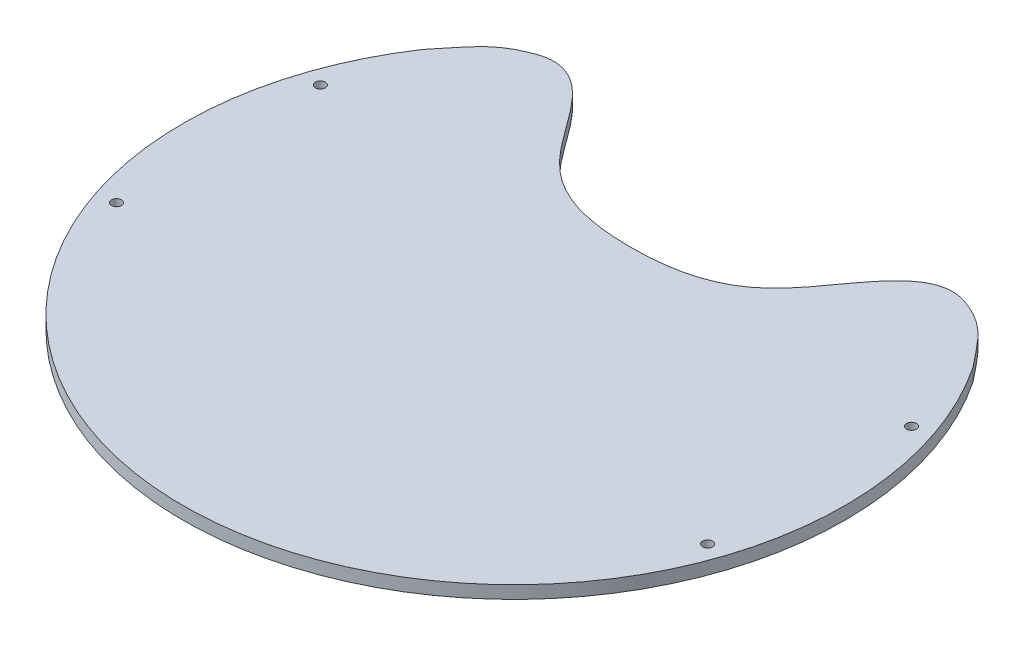
SolidWorks part; units mm, degrees
material "ABS"
ref_plane "Front Plane" through (0, 0, 0) normal (0, 0, 1) x (1, 0, 0)
ref_plane "Top Plane" through (0, 0, 0) normal (0, 1, 0) x (1, 0, 0)
ref_plane "Right Plane" through (0, 0, 0) normal (1, 0, 0) x (0, 0, -1)
sketch "Sketch1" plane through (0, 0, 0) normal (0, 1, 0) x (1, 0, 0)
  circle A0 centre (0, 0) radius 164.975
  dimension "D1" = 329.95
extrude "Boss-Extrude1" add sketch "Sketch1" along normal blind 6.35
ref_point "Point1"
sketch "Sketch2" plane through (0, 0, 0) normal (0, -1, 0) x (1, 0, 0)
  line L0 (0, -1000) -> (0, 49000) construction
  line L1 (-1000, 0) -> (49000, 0) construction
  circle A0 centre (147.32, -50.8) radius 4.7625 construction
  circle A1 centre (147.32, 50.8) radius 4.7625 construction
  circle A2 centre (-147.32, -50.8) radius 4.7625 construction
  circle A3 centre (-147.32, 50.8) radius 4.7625 construction
  point P0 (147.32, -50.8)
  dimension "D1" = 147.32
  dimension "D2" = 50.8
hole_wizard "#10 Clearance Hole1" positions "Sketch4" profile "Sketch3" hole size "#10" standard "Ansi Inch" end condition through all
sketch "Sketch4" plane through (0, 6.35, 0) normal (0, 1, 0) x (-1, 0, 0)
  point P1 (147.32, 50.8)
  point P4 (147.32, -50.8)
  point P7 (-147.32, -50.8)
  point P10 (-147.32, 50.8)
sketch "Sketch3" plane through (-147.32, 6.35, 50.8) normal (1, 0, 0) x (0, 0, 1)
  line L0 (0, 0) -> (0, 6.35)
  line L1 (0, 6.35) -> (2.4892, 6.35)
  line L2 (2.4892, 6.35) -> (2.4892, 0)
  line L5 (2.4892, 0) -> (0, 0)
  line L11 (0, -6.35) -> (0, 107.95) construction
  dimension "Thru Hole Dia." = 4.9784
  dimension "Thru Hole Depth" = 6.35
sketch "Sketch5" plane through (0, 6.35, 0) normal (0, 1, 0) x (1, 0, 0)
  line L0 (0, 201000) -> (0, -249000) construction
  line L1 (-50.8, -55.3589) -> (50.8, -55.3589) construction
  line L2 (-50.8, -55.3589) -> (-50.8, -156.9589) construction
  line L3 (-50.8, -156.9589) -> (50.8, -156.9589) construction
  line L4 (50.8, -55.3589) -> (50.8, -156.9589) construction
  line L5 (-50.8, -55.3589) -> (50.8, -156.9589) construction
  line L6 (-50.8, -156.9589) -> (50.8, -55.3589) construction
  line L7 (0, -106.1589) -> (0, 58.1068) construction
  circle A0 centre (0, 0) radius 164.975 construction
  circle A2 centre (147.32, 50.8) radius 2.4892 construction
  spline S0 degree 3 poles (-137.1735, 91.6525) (-125.7052, 105.9966) (-120.8705, 112.2721) (-90.3531, 124.7653) (-63.3632, 88.0034) (-42.1548, 58.1068) (0, 58.1068) knots 0 0 0 0 0.216331 0.275014 0.586828 1 1 1 1
  spline S1 degree 3 poles (137.1735, 91.6525) (125.7052, 105.9966) (120.8705, 112.2721) (90.3531, 124.7653) (63.3632, 88.0034) (42.1548, 58.1068) (0, 58.1068) knots 0 0 0 0 0.216331 0.275014 0.586828 1 1 1 1
  point P0 (0, -106.1589)
  dimension "D1" = 101.6
  dimension "D2" = 101.6
extrude "Cut-Extrude1" cut sketch "Sketch5" against normal through all and the other way through all contours S0 S1
